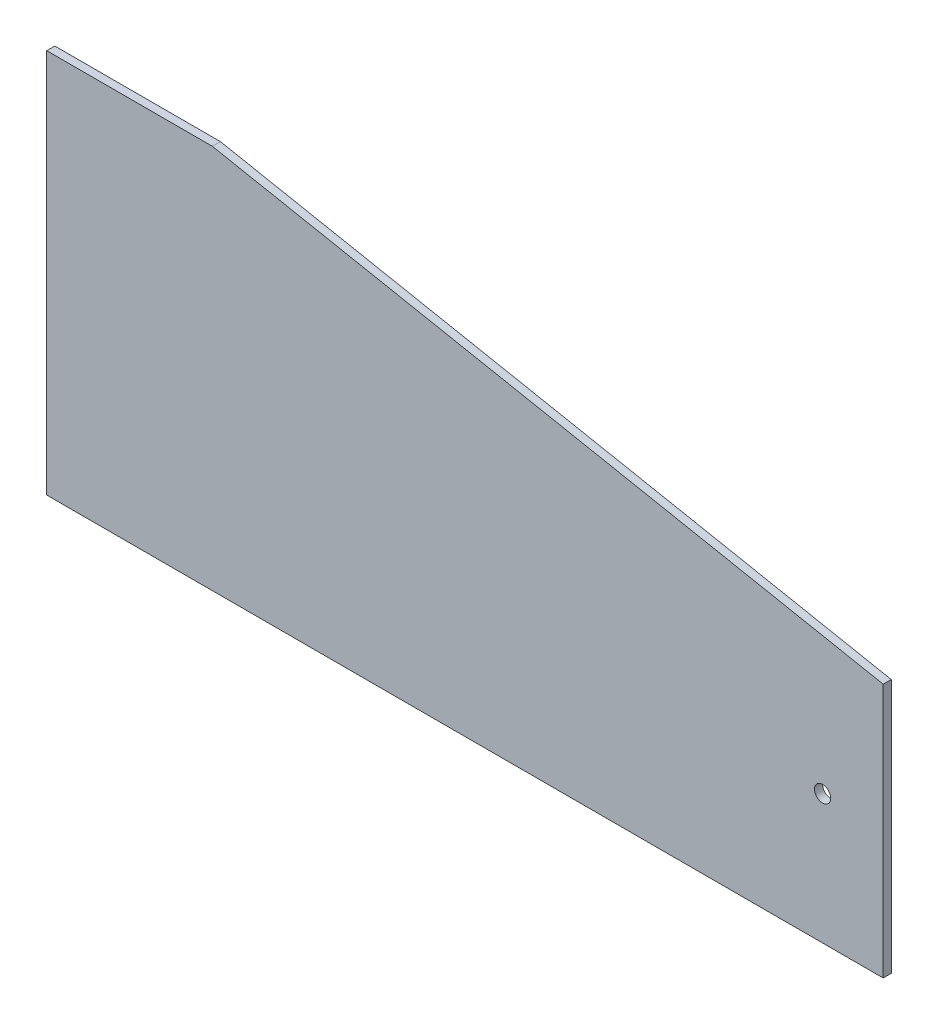
SolidWorks part; units mm, degrees
material "Pine"
ref_plane "Front Plane" through (0, 0, 0) normal (0, 0, 1) x (1, 0, 0)
ref_plane "Top Plane" through (0, 0, 0) normal (0, 1, 0) x (1, 0, 0)
ref_plane "Right Plane" through (0, 0, 0) normal (1, 0, 0) x (0, 0, -1)
sketch "Sketch1" plane through (0, 0, 0) normal (0, 0, 1) x (1, 0, 0)
  line L0 (0, 0) -> (0, 605)
  line L1 (0, 605) -> (260.3664, 605)
  line L2 (260.3664, 605) -> (1315, 400)
  line L3 (1315, 400) -> (1315, 0)
  line L4 (1315, 0) -> (0, 0)
  dimension "D1" = 90
  dimension "D2" = 79
  dimension "D3" = 400
  dimension "D4" = 1315
  dimension "D5" = 605
  dimension "D6" = 90
extrude "Boss-Extrude1" add sketch "Sketch1" along normal blind 12.7
sketch "Sketch2" plane through (0, 0, 0) normal (0, 0, -1) x (-1, 0, 0)
  line L0 (-1315, 0) -> (-1315, 400) construction
  line L1 (0, 0) -> (-1315, 0) construction
  circle A0 centre (-1219.75, 203.2) radius 12.7
  dimension "D3" = 25.4
  dimension "D1" = 95.25
  dimension "D2" = 203.2
extrude "Cut-Extrude1" cut sketch "Sketch2" against normal blind 203.2
